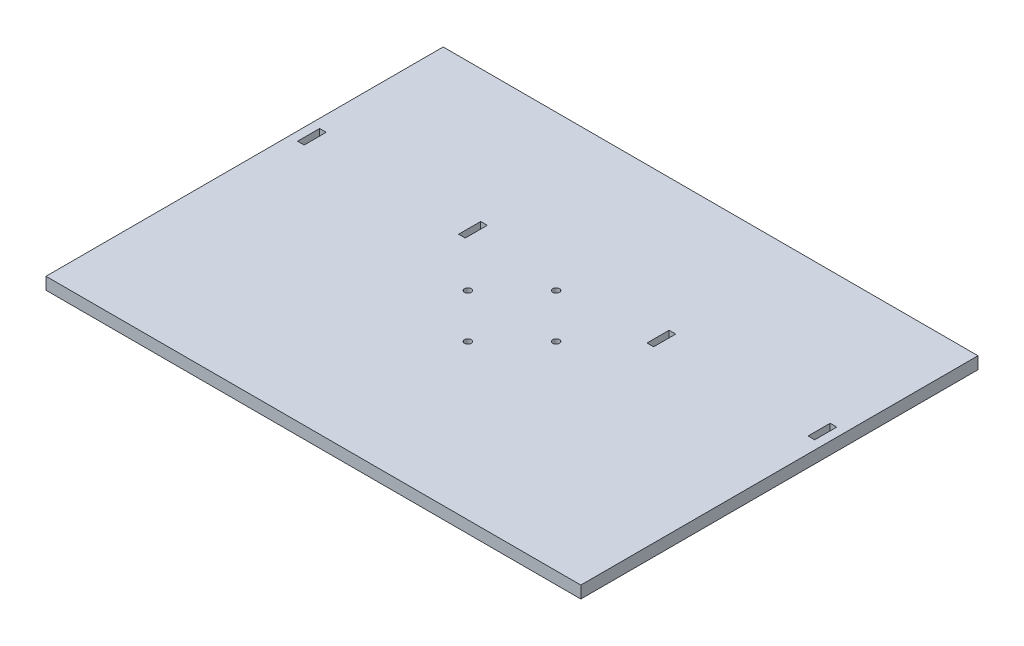
SolidWorks part; units mm, degrees
ref_plane "Alzado" through (0, 0, 0) normal (0, 0, 1) x (1, 0, 0)
ref_plane "Planta" through (0, 0, 0) normal (0, 1, 0) x (1, 0, 0)
ref_plane "Vista lateral" through (0, 0, 0) normal (1, 0, 0) x (0, 0, -1)
sketch "Croquis1" plane through (0, 0, 0) normal (0, 1, 0) x (1, 0, 0)
  line L1 (-70, 55) -> (70, 55)
  line L2 (-70, 55) -> (-70, -55)
  line L3 (-70, -55) -> (70, -55)
  line L4 (70, 55) -> (70, -55)
  line L5 (-70, 55) -> (70, -55) construction
  line L6 (-70, -55) -> (70, 55) construction
  circle A0 centre (0, 20) radius 1.75
  circle A1 centre (20, 0) radius 1.7
  circle A2 centre (-20, 0) radius 1.7
  circle A3 centre (0, -20) radius 1.7
  point P9 (0, 0)
  dimension "D1" = 3.5
  dimension "D3" = 20
  dimension "D4" = 20
  dimension "D5" = 20
  dimension "D2" = 20
  dimension "D6" = 110
  dimension "D7" = 140
extrude "Saliente-Extruir1" add sketch "Croquis1" along normal blind 6
fillet "Redondeo1" radius 8 3 edges at (-70, 3, -55) (70, 3, 55) (-70, 3, 55)
fillet "Redondeo2" radius 8 1 edges at (70, 3, -55)
sketch "Croquis2" plane through (0, 6, 0) normal (0, 1, 0) x (1, 0, 0)
  line L0 (62, 55) -> (-62, 55) construction
  line L1 (-43, 55) -> (-85.6723, 55)
  line L2 (-43, 55) -> (-43, -57.1974)
  line L3 (-43, -57.1974) -> (-85.6723, -57.1974)
  line L4 (-85.6723, 55) -> (-85.6723, -57.1974)
  point P6 (-43, -1.0987)
  dimension "D1" = 43
extrude "Cortar-Extruir1" cut sketch "Croquis2" against normal blind 10
sketch "Croquis3" plane through (0, 6, 0) normal (0, 1, 0) x (1, 0, 0)
  line L0 (62, 55) -> (-43, 55) construction
  line L1 (50.7596, 55) -> (87, 55)
  line L2 (50.7596, 55) -> (50.7596, -55)
  line L3 (50.7596, -55) -> (87, -55)
  line L4 (87, 55) -> (87, -55)
  line L5 (-43, -55) -> (-43, 55) construction
  dimension "D1" = 130
extrude "Saliente-Extruir2" add sketch "Croquis3" against normal blind 6
sketch "Croquis4" plane through (0, 6, 0) normal (0, 1, 0) x (1, 0, 0)
  line L0 (-43, -55) -> (-43, 55) construction
  line L1 (-43, -42.6571) -> (87, -42.6571)
  line L2 (-43, -42.6571) -> (-43, -87)
  line L3 (-43, -87) -> (87, -87)
  line L4 (87, -42.6571) -> (87, -87)
  line L6 (-43, 42.684) -> (87, 42.684)
  line L7 (-43, 42.684) -> (-43, 87)
  line L8 (-43, 87) -> (87, 87)
  line L9 (87, 42.684) -> (87, 87)
  dimension "D1" = 87
  dimension "D2" = 87
extrude "Saliente-Extruir3" add sketch "Croquis4" against normal blind 6
fillet "Redondeo3" radius 10 3 edges at (-43, 3, 87) (87, 3, -87) (87, 3, 87)
fillet "Redondeo4" radius 10 1 edges at (-43, 3, -87)
sketch "Croquis5" plane through (0, 6, 0) normal (0, 1, 0) x (1, 0, 0)
  line L0 (-54.7776, 71.4102) -> (-44.6398, 116.6193)
  line L1 (-44.6398, 116.6193) -> (127.0199, 109.6238)
  line L2 (127.0199, 109.6238) -> (127.0199, -105.0853)
  line L3 (127.0199, -105.0853) -> (10.7864, -105.0853)
  line L4 (10.7864, -105.0853) -> (9.1897, -89.5296)
  circle A0 centre (0, 0) radius 90
  line M1 (77, 87) -> (-33, 87)
  arc M2 (-33, 87) -> (-43, 77) centre (-33, 77) ccw
  arc M4 (-43, -77) -> (-33, -87) centre (-33, -77) ccw
  line M5 (-33, -87) -> (77, -87)
  arc M6 (77, -87) -> (87, -77) centre (77, -77) ccw
  line M7 (87, -77) -> (87, 77)
  arc M8 (87, 77) -> (77, 87) centre (77, 77) ccw
  dimension "D1" = 180
extrude "Cortar-Extruir2" cut sketch "Croquis5" against normal blind 10 contours A0 M7 M8 M1 | A0 M5 M6 M7 | A0 M1 M2 | A0 M4 M5
sketch "Croquis6" plane through (0, 6, 0) normal (0, 1, 0) x (1, 0, 0)
  line L0 (47.9455, -76.1658) -> (-35.5656, -82.6746)
  line L1 (72.0806, 53.8923) -> (75.3723, -49.1834)
  line L2 (-39.173, 81.0276) -> (47.9455, 76.1658)
  circle A0 centre (0, 0) radius 90
  line M5 (-23.0434, -87) -> (23.0434, -87)
  arc M6 (23.0434, -87) -> (87, -23.0434) centre (0, 0) ccw
  line M7 (87, -23.0434) -> (87, 23.0434)
  arc M8 (87, 23.0434) -> (23.0434, 87) centre (0, 0) ccw
  line M9 (23.0434, 87) -> (-23.0434, 87)
  arc M10 (-23.0434, 87) -> (-42.756, 79.1955) centre (0, 0) ccw
  arc M14 (-42.756, -79.1955) -> (-23.0434, -87) centre (0, 0) ccw
extrude "Saliente-Extruir4" add sketch "Croquis6" against normal blind 6 contours L2 M10 M8 M9 | A0 M9 | A0 M7 | L1 M8 M6 M7 | L0 M6 M14 M5 | A0 M5
sketch "Croquis7" plane through (0, 6, 0) normal (0, 1, 0) x (1, 0, 0)
  line L2 (0, -90) -> (-49.2462, -90) construction
  line L3 (-42.9388, -78.1045) -> (-42.9388, -90) construction
  line L5 (-42.9388, -90) -> (199.4427, -90)
  line L6 (-42.9388, -90) -> (-42.9388, 90)
  line L7 (-42.9388, 90) -> (199.4427, 90)
  line L8 (199.4427, -90) -> (199.4427, 90)
  arc A4 (-42.756, -79.1955) -> (-42.756, 79.1955) centre (0, 0) ccw construction
  arc A5 (-43, -77) -> (-42.756, -79.1955) centre (-33, -77) ccw construction
extrude "Saliente-Extruir5" add sketch "Croquis7" along normal blind 5.5
sketch "Croquis8" plane through (0, 6, 0) normal (0, -1, 0) x (-1, 0, 0)
  line L0 (-199.4427, -90) -> (42.9388, 90) construction
  line L1 (42.9388, -90) -> (-199.4427, 90) construction
  circle A0 centre (-98.252, 0) radius 1.5
  circle A1 centre (-78.252, 20) radius 1.5
  circle A2 centre (-58.252, 0) radius 1.5
  circle A3 centre (-78.252, -20) radius 1.5
  point P16 (-78.252, 0)
  dimension "D1" = 20
  dimension "D2" = 20
  dimension "D3" = 20
  dimension "D4" = 20
extrude "Cortar-Extruir3" cut sketch "Croquis8" against normal blind 5.5
sketch "Croquis9" plane through (0, 0, 0) normal (0, -1, 0) x (-1, 0, 0)
  line L1 (102.9319, -118.2528) -> (-124.2285, -118.2528)
  line L2 (102.9319, -118.2528) -> (102.9319, 132.6301)
  line L3 (102.9319, 132.6301) -> (-124.2285, 132.6301)
  line L4 (-124.2285, -118.2528) -> (-124.2285, 132.6301)
extrude "Cortar-Extruir5" cut sketch "Croquis9" against normal blind 6
sketch "Croquis10" plane through (0, 6, 0) normal (0, -1, 0) x (-1, 0, 0)
  line L0 (42.9388, 90) -> (42.9388, -90) construction
  line L1 (38.9388, 20) -> (35.9388, 20)
  line L2 (38.9388, 20) -> (38.9388, 30)
  line L3 (38.9388, 30) -> (35.9388, 30)
  line L4 (35.9388, 20) -> (35.9388, 30)
  line L5 (-195.4427, 30) -> (-192.4427, 30)
  line L6 (-195.4427, 30) -> (-195.4427, 20)
  line L7 (-195.4427, 20) -> (-192.4427, 20)
  line L8 (-192.4427, 30) -> (-192.4427, 20)
  line L9 (-34.0612, 30) -> (-37.0612, 30)
  line L10 (-34.0612, 30) -> (-34.0612, 20)
  line L11 (-34.0612, 20) -> (-37.0612, 20)
  line L12 (-37.0612, 30) -> (-37.0612, 20)
  line L13 (-199.4427, -90) -> (-199.4427, 90) construction
  line L14 (-199.4427, 90) -> (42.9388, 90) construction
  line L16 (-122.4427, 30) -> (-119.4427, 30)
  line L17 (-122.4427, 30) -> (-122.4427, 20)
  line L18 (-122.4427, 20) -> (-119.4427, 20)
  line L19 (-119.4427, 30) -> (-119.4427, 20)
  point P12 (38.9388, 25)
  dimension "D1" = 4
  dimension "D2" = 4
  dimension "D3" = 70
  dimension "D4" = 3
  dimension "D5" = 70
  dimension "D6" = 10
  dimension "D7" = 0
  dimension "D8" = 0
  dimension "D9" = 10
  dimension "D10" = 10
  dimension "D11" = 70
extrude "Cortar-Extruir6" cut sketch "Croquis10" against normal blind 6
